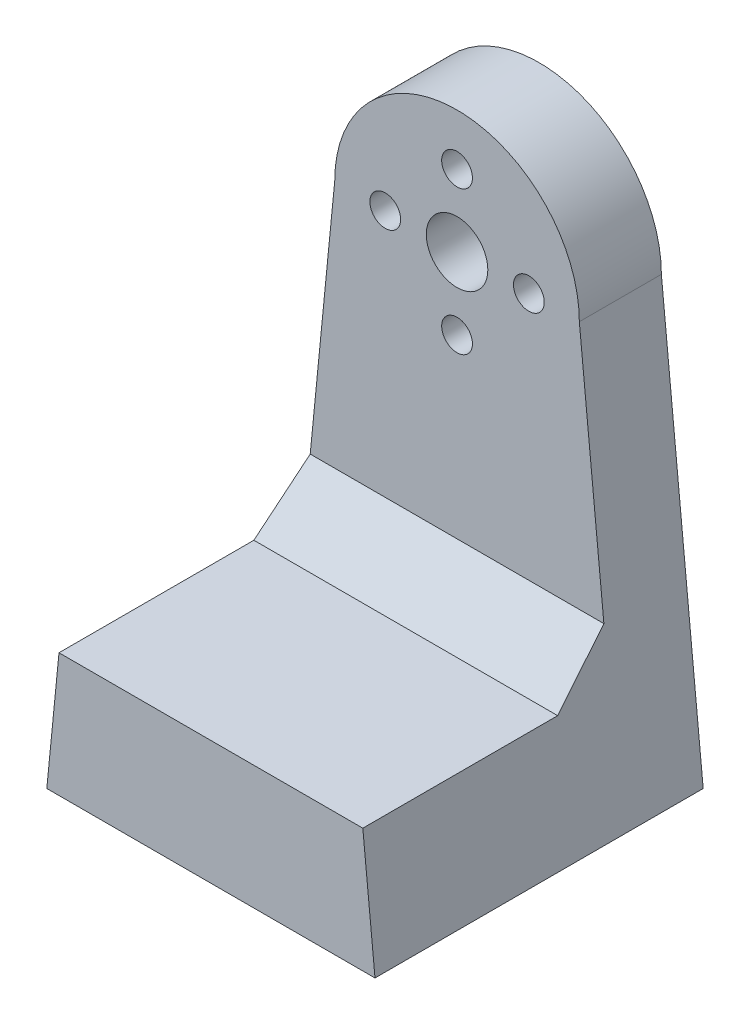
SolidWorks part; units mm, degrees
ref_plane "Alzado" through (0, 0, 0) normal (0, 0, 1) x (1, 0, 0)
ref_plane "Planta" through (0, 0, 0) normal (0, 1, 0) x (1, 0, 0)
ref_plane "Vista lateral" through (0, 0, 0) normal (1, 0, 0) x (0, 0, -1)
sketch "Croquis1" plane through (0, 0, 0) normal (0, 1, 0) x (1, 0, 0)
  line L1 (-16, -16) -> (16, -16)
  line L2 (-16, -16) -> (-16, 16)
  line L3 (-16, 16) -> (16, 16)
  line L4 (16, -16) -> (16, 16)
  line L5 (-16, -16) -> (16, 16) construction
  line L6 (-16, 16) -> (16, -16) construction
  point P0 (0, 0)
  dimension "D1" = 32
extrude "Saliente-Extruir1" add sketch "Croquis1" along normal blind 42
sketch "Croquis2" plane through (16, 0, 0) normal (1, 0, 0) x (0, 0, -1)
  line L0 (-16, 12.058) -> (3, 12.058)
  line L1 (-16, 42) -> (-16, 0) construction
  line L2 (3, 12.058) -> (8, 17.0819)
  line L3 (8, 17.0819) -> (8, 42)
  line L4 (-16, 42) -> (16, 42) construction
  line L5 (8, 42) -> (-16, 42)
  line L6 (-16, 42) -> (-16, 12.058)
  line L7 (-16, 0) -> (16, 0) construction
  line L9 (16, 42) -> (16, 0) construction
  dimension "D1" = 19
  dimension "D2" = 12.058
  dimension "D3" = 7.088
  dimension "D4" = 8
extrude "Cortar-Extruir1" cut sketch "Croquis2" against normal blind 42
sketch "Croquis3" plane through (16, 0, 0) normal (1, 0, 0) x (0, 0, -1)
  line L1 (8, 41.3759) -> (16, 41.3759)
  line L2 (16, 42) -> (16, 0) construction
  line L3 (16, 41.3759) -> (16, 42)
  line L4 (16, 42) -> (8, 42)
  line L5 (8, 42) -> (8, 41.3759)
extrude "Cortar-Extruir2" cut sketch "Croquis3" against normal blind 42
sketch "Croquis6" plane through (0, 0, 16) normal (0, 0, 1) x (1, 0, 0)
  line L0 (-16, 0) -> (-11.9226, 41.3759)
  line L1 (16, 41.3759) -> (-16, 41.3759) construction
  line L2 (-16, 0) -> (16, 0) construction
  line L3 (16, 0) -> (11.9226, 41.3759)
  line L4 (-11.9226, 41.3759) -> (-16, 41.3759)
  line L5 (-16, 41.3759) -> (-16, 0)
  line L6 (11.9226, 41.3759) -> (16, 41.3759)
  line L7 (16, 41.3759) -> (16, 0)
  dimension "D1" = 84.372
  dimension "D2" = 84.372
extrude "Cortar-Extruir3" cut sketch "Croquis6" against normal through all
sketch "Croquis7" plane through (0, 0, -16) normal (0, 0, -1) x (-1, 0, 0)
  line L0 (11.9226, 41.3759) -> (-11.9226, 41.3759) construction
  circle A0 centre (0, 41.3759) radius 11.9226
extrude "Saliente-Extruir3" add sketch "Croquis7" against normal blind 8
sketch "Croquis8" plane through (0, 0, -8) normal (0, 0, 1) x (1, 0, 0)
  circle A0 centre (0, 41.2986) radius 3
  arc A1 (11.9226, 41.3759) -> (-11.9226, 41.3759) centre (0, 41.3759) ccw construction
  circle A2 centre (0, 48.2986) radius 1.5
  circle A3 centre (7, 41.2986) radius 1.5
  circle A4 centre (0, 34.2986) radius 1.5
  circle A5 centre (-7, 41.2986) radius 1.5
  point P5 (0, 53.2986)
  point P17 (0, 41.2986)
  dimension "D2" = 6
  dimension "D3" = 3
  dimension "D1" = 12
  dimension "D4" = 7
  dimension "D6" = 7
  dimension "D7" = 7
  dimension "D8" = 7
  dimension "D5" = 4
extrude "Cortar-Extruir5" cut sketch "Croquis8" against normal through all
sketch "Croquis9" plane through (0, 0, 0) normal (0, -1, 0) x (1, 0, 0)
  line L0 (-16, 16) -> (16, 16) construction
  line L1 (-16, -16) -> (-16, 16) construction
  circle A0 centre (-8, 7.5) radius 2.05
  circle A1 centre (8, 7.5) radius 2.05
  dimension "D2" = 4.1
  dimension "D1" = 16
  dimension "D3" = 8.5
  dimension "D4" = 8
extrude "Cortar-Extruir6" cut sketch "Croquis9" against normal blind 6
